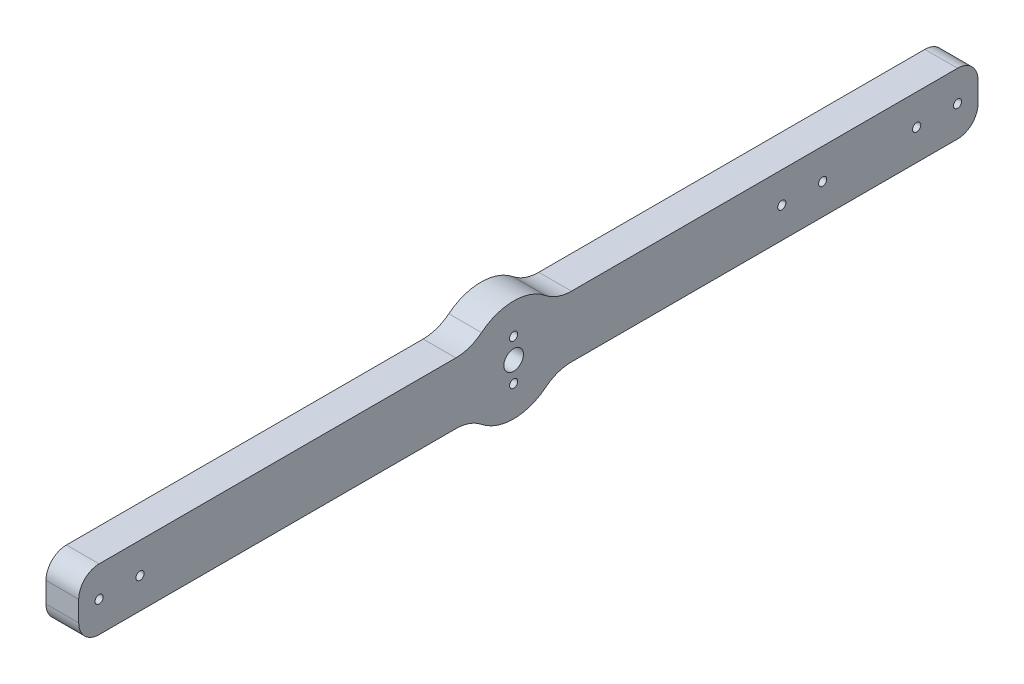
SolidWorks part; units mm, degrees
ref_plane "前视基准面" through (0, 0, 0) normal (0, 0, 1) x (1, 0, 0)
ref_plane "上视基准面" through (0, 0, 0) normal (0, 1, 0) x (1, 0, 0)
ref_plane "右视基准面" through (0, 0, 0) normal (1, 0, 0) x (0, 0, -1)
other "Configuration Table"
sketch "草图1" plane through (0, 0, 0) normal (1, 0, 0) x (0, 0, -1)
  line L1 (0, 0) -> (120, 0)
  line L2 (0, 0) -> (0, 15)
  line L3 (0, 15) -> (120, 15)
  line L4 (120, 0) -> (120, 15)
  dimension "D1" = 15
  dimension "D2" = 120
extrude "凸台-拉伸1" add sketch "草图1" along normal blind 8
fillet "圆角1" radius 5 4 edges at (4, 0, -120) (4, 15, -120) (4, 0, 0) (4, 15, 0)
sketch "草图6" plane through (8, 0, 0) normal (1, 0, 0) x (0, 0, -1)
  circle A0 centre (6.4, 7.5) radius 12.5
extrude "凸台-拉伸2" add sketch "草图6" against normal up to surface (8 mm away) up to face at (0, 7.5, -60)
sketch "草图7" plane through (0, 0, 0) normal (-1, 0, 0) x (0, 0, 1)
  line L0 (-6.4, 7.5) -> (-6.4, 18.561) construction
  circle A0 centre (-6.4, 12.5) radius 1
  circle A1 centre (-6.4, 2.5) radius 1
  dimension "D3" = 2
  dimension "D4" = 2
  dimension "D1" = 10
  dimension "D2" = 5
extrude "切除-拉伸4" cut sketch "草图7" against normal blind 23
sketch "草图8" plane through (0, 0, 0) normal (-1, 0, 0) x (0, 0, 1)
  line L0 (-6.4, 12.5) -> (-6.4, 2.5) construction
  circle A0 centre (-6.4, 7.5) radius 2.4
  dimension "D1" = 4.8
extrude "切除-拉伸5" cut sketch "草图8" against normal blind 23
sketch "草图9" plane through (0, 0, 0) normal (0, 0, 1) x (1, 0, 0)
  line L0 (0, 20) -> (0, -5) construction
  line L1 (0, 15) -> (8, 15)
  line L2 (0, 15) -> (0, 0)
  line L3 (0, 0) -> (8, 0)
  line L4 (8, 15) -> (8, 0)
  line L5 (2.5, 7.5) -> (0, 7.5) construction
  dimension "D1" = 15
  dimension "D2" = 7.5
  dimension "D3" = 8
extrude "凸台-拉伸3" add sketch "草图9" along normal blind 100
sketch "草图10" plane through (0, 0, 0) normal (-1, 0, 0) x (0, 0, 1)
  line L0 (-6.4, 7.5) -> (29.4071, 7.5) construction
  line L2 (3.523, 10.5) -> (28.523, 10.5)
  line L3 (3.523, 10.5) -> (3.523, 4.5)
  line L4 (3.523, 4.5) -> (28.523, 4.5)
  line L5 (28.523, 10.5) -> (28.523, 4.5)
  dimension "D1" = 6
  dimension "D2" = 3
  dimension "D3" = 25
extrude "切除-拉伸6" cut sketch "草图10" against normal blind 5
sketch "草图4" plane through (0, 0, 0) normal (0, 0, 1) x (1, 0, 0)
  circle A0 centre (2.5, 7.5) radius 1
  dimension "D1" = 2
extrude "切除-拉伸7" cut sketch "草图4" against normal blind 15 and the other way blind 7
fillet "圆角2" radius 10 4 edges at (4, 15, -16.4) (4, 0, -16.4) (4, 0, 3.6) (4, 15, 3.6)
fillet "圆角4" radius 5 2 edges at (4, 0, 100) (4, 15, 100)
sketch "草图12" plane through (0, 0, 0) normal (-1, 0, 0) x (0, 0, 1)
  line L0 (-120, 7.5) -> (-68.9388, 7.5) construction
  line L1 (-120, 5) -> (-120, 10) construction
  line L2 (100, 7.5) -> (76.6337, 7.5) construction
  line L3 (100, 10) -> (100, 5) construction
  circle A0 centre (-115, 7.5) radius 1
  circle A1 centre (-105, 7.5) radius 1
  circle A2 centre (-82, 7.5) radius 1
  circle A3 centre (-72, 7.5) radius 1
  circle A4 centre (95, 7.5) radius 1
  circle A5 centre (85, 7.5) radius 1
  point P22 (100, 6.5394)
  point P23 (100, 6.4029)
  point P24 (98.0697, 6.4484)
  dimension "D2" = 2
  dimension "D3" = 2
  dimension "D5" = 2
  dimension "D6" = 2
  dimension "D9" = 2
  dimension "D10" = 2
  dimension "D1" = 10
  dimension "D4" = 5
  dimension "D7" = 10
  dimension "D8" = 23
  dimension "D11" = 10
  dimension "D12" = 5
extrude "切除-拉伸8" cut sketch "草图12" against normal up to next
